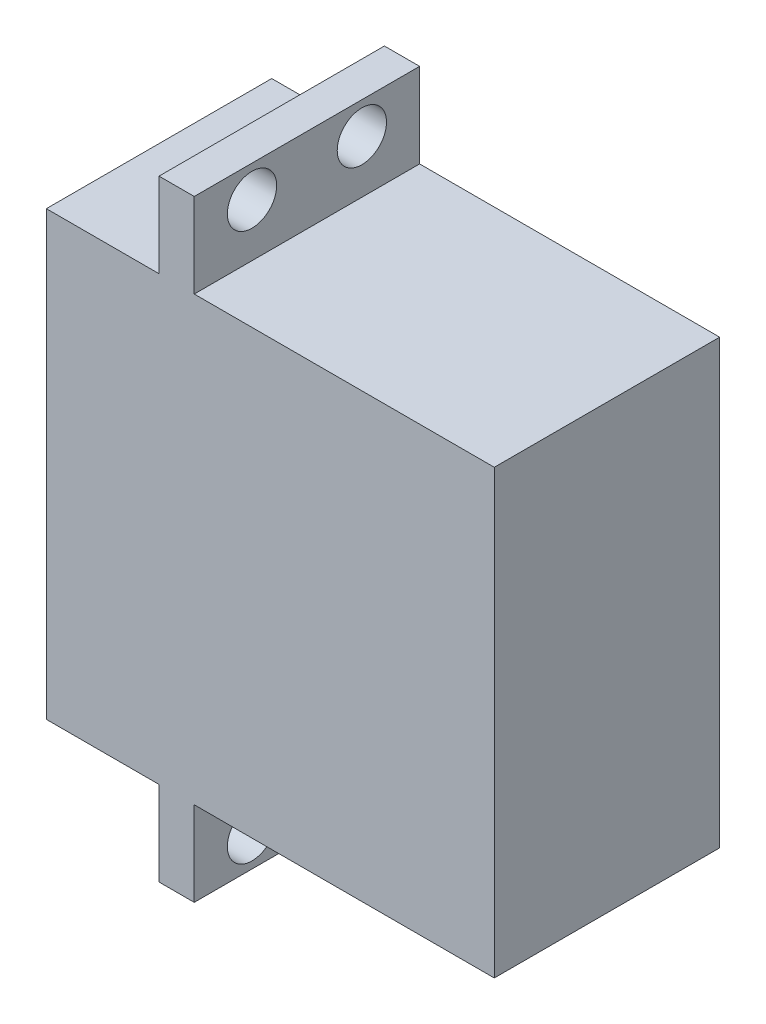
SolidWorks part; units mm, degrees
ref_plane "Front Plane" through (0, 0, 0) normal (0, 0, 1) x (1, 0, 0)
ref_plane "Top Plane" through (0, 0, 0) normal (0, 1, 0) x (1, 0, 0)
ref_plane "Right Plane" through (0, 0, 0) normal (1, 0, 0) x (0, 0, -1)
sketch "Sketch1" plane through (0, 0, 0) normal (0, 0, 1) x (1, 0, 0)
  line L1 (0, 0) -> (40.386, 0)
  line L2 (0, 0) -> (0, 39.878)
  line L3 (0, 39.878) -> (40.386, 39.878)
  line L4 (40.386, 0) -> (40.386, 39.878)
  dimension "D1" = 40.386
  dimension "D2" = 39.878
extrude "Boss-Extrude1" add sketch "Sketch1" along normal blind 20.32
sketch "Sketch2" plane through (0, 0, 0) normal (-1, 0, 0) x (0, 0, 1)
  line L0 (10.16, 30.607) -> (10.16, 39.878) construction
  line L1 (20.32, 39.878) -> (0, 39.878) construction
  line L2 (10.16, 30.607) -> (20.32, 30.607) construction
  line L3 (20.32, 39.878) -> (20.32, 0) construction
  circle A0 centre (10.16, 30.607) radius 2.9464
  dimension "D1" = 5.8928
  dimension "D2" = 9.271
extrude "Boss-Extrude2" add sketch "Sketch2" along normal blind 5.08
sketch "Sketch3" plane through (0, 39.878, 0) normal (0, 1, 0) x (1, 0, 0)
  line L0 (40.386, -20.32) -> (0, -20.32) construction
  line L1 (10.16, -20.32) -> (13.335, -20.32)
  line L2 (10.16, -20.32) -> (10.16, 0)
  line L3 (10.16, 0) -> (13.335, 0)
  line L4 (13.335, -20.32) -> (13.335, 0)
  line L5 (40.386, 0) -> (0, 0) construction
  line L6 (0, -20.32) -> (0, 0) construction
  dimension "D1" = 10.16
  dimension "D2" = 3.175
extrude "Boss-Extrude3" add sketch "Sketch3" along normal blind 7.62
sketch "Sketch4" plane through (0, 0, 0) normal (0, -1, 0) x (1, 0, 0)
  line L0 (0, 0) -> (40.386, 0) construction
  line L1 (10.16, 0) -> (13.335, 0)
  line L2 (10.16, 0) -> (10.16, 20.32)
  line L3 (10.16, 20.32) -> (13.335, 20.32)
  line L4 (13.335, 0) -> (13.335, 20.32)
  line L5 (0, 20.32) -> (40.386, 20.32) construction
  line L6 (0, 20.32) -> (0, 0) construction
  dimension "D1" = 10.16
  dimension "D2" = 3.175
extrude "Boss-Extrude4" add sketch "Sketch4" along normal blind 7.62
sketch "Sketch5" plane through (10.16, 0, 0) normal (-1, 0, 0) x (0, 0, 1)
  line L0 (10.16, 44.6405) -> (10.16, 39.878) construction
  line L3 (10.16, 44.6405) -> (15.113, 44.6405) construction
  line L4 (10.16, 44.6405) -> (5.207, 44.6405) construction
  line L5 (0, 39.878) -> (20.32, 39.878) construction
  circle A0 centre (5.207, 44.6405) radius 2.2225
  circle A1 centre (15.113, 44.6405) radius 2.2225
  dimension "D2" = 4.445
  dimension "D3" = 4.445
  dimension "D1" = 9.906
  dimension "D4" = 4.7625
extrude "Cut-Extrude1" cut sketch "Sketch5" against normal through all
sketch "Sketch6" plane through (-5.08, 0, 0) normal (-1, 0, 0) x (0, 0, 1)
  circle A0 centre (10.16, 30.607) radius 1.5875
  circle A1 centre (10.16, 30.607) radius 2.9464 construction
  dimension "D1" = 3.175
extrude "Cut-Extrude2" cut sketch "Sketch6" against normal blind 6.35
sketch "Sketch7" plane through (10.16, 0, 0) normal (-1, 0, 0) x (0, 0, 1)
  line L0 (10.16, -4.7625) -> (10.16, 0) construction
  line L3 (10.16, -4.7625) -> (15.113, -4.7625) construction
  line L4 (10.16, -4.7625) -> (5.207, -4.7625) construction
  line L5 (20.32, 0) -> (0, 0) construction
  circle A0 centre (15.113, -4.7625) radius 2.2225
  circle A1 centre (5.207, -4.7625) radius 2.2225
  dimension "D1" = 4.445
  dimension "D2" = 4.445
  dimension "D4" = 9.906
  dimension "D5" = 4.7625
extrude "Cut-Extrude3" cut sketch "Sketch7" against normal through all
